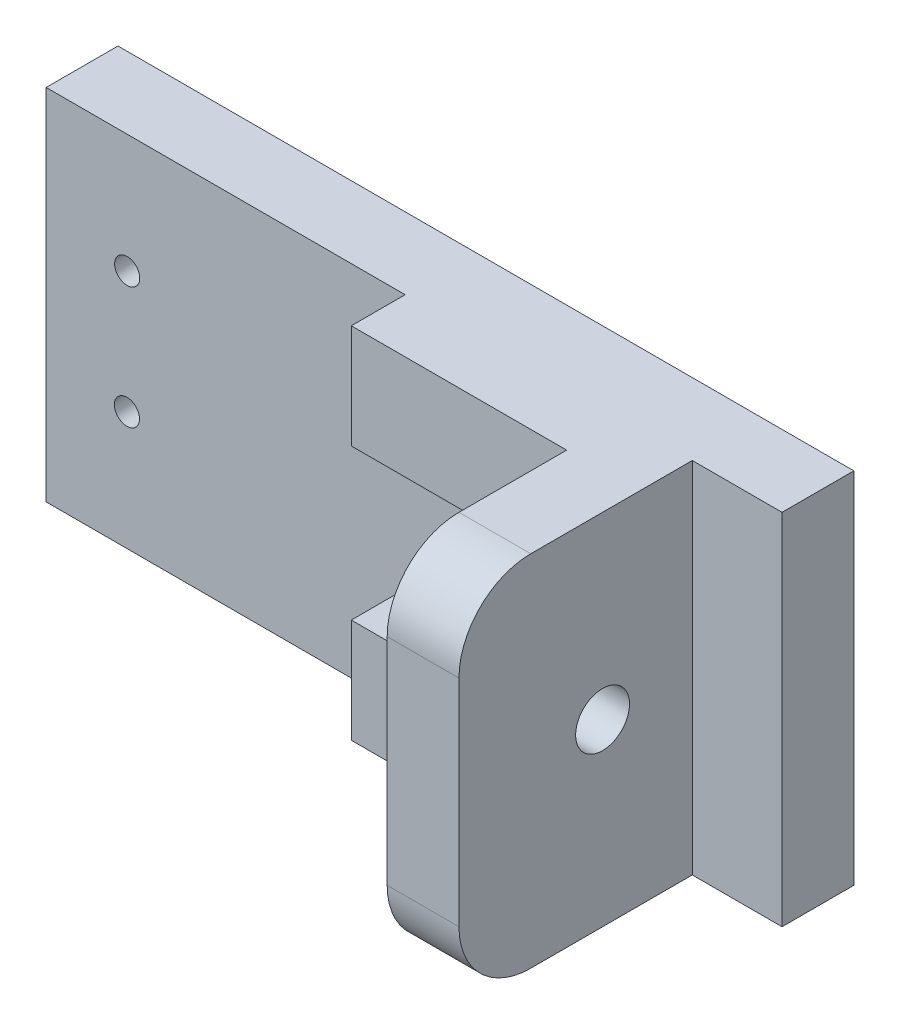
SolidWorks part; units mm, degrees
ref_plane "Piano frontale" through (0, 0, 0) normal (0, 0, 1) x (1, 0, 0)
ref_plane "Piano superiore" through (0, 0, 0) normal (0, 1, 0) x (1, 0, 0)
ref_plane "Piano destro" through (0, 0, 0) normal (1, 0, 0) x (0, 0, -1)
sketch "Schizzo1" plane through (0, 0, 0) normal (0, 0, 1) x (1, 0, 0)
  line L1 (-102.5, -50) -> (102.5, -50)
  line L2 (-102.5, -50) -> (-102.5, 50)
  line L3 (-102.5, 50) -> (102.5, 50)
  line L4 (102.5, -50) -> (102.5, 50)
  line L5 (-102.5, -50) -> (102.5, 50) construction
  line L6 (-102.5, 50) -> (102.5, -50) construction
  point P0 (0, 0)
  dimension "D1" = 205
  dimension "D2" = 100
extrude "Estrusione-Estrusione1" add sketch "Schizzo1" along normal blind 20
sketch "Schizzo2" plane through (0, 0, 0) normal (0, 0, 1) x (1, 0, 0)
  line L0 (-102.5, 50) -> (-102.5, -50) construction
  line L2 (-102.5, -50) -> (102.5, -50) construction
  circle A0 centre (-80, -17) radius 9.7421
  circle A1 centre (-79.9317, 16.9999) radius 9.7421
  dimension "D1" = 22.5
  dimension "D2" = 33
  dimension "D3" = 34
hole_wizard "Foro filettato M8x1.0-1" positions "Schizzo3" profile "Schizzo4" tap size "M8x1.0" standard "IS" end condition through all
sketch "Schizzo3" plane through (0, 0, 0) normal (0, 0, -1) x (-1, 0, 0)
  point P0 (79.9317, 16.9999)
  point P3 (80, -17)
cosmetic thread "Filettatura del foro1" parameters "D2"=8
cosmetic thread "Filettatura del foro2" parameters "D2"=8
sketch "Schizzo4" plane through (-79.9317, 16.9999, 0) normal (1, 0, 0) x (0, 1, 0)
  line L0 (0, 0) -> (0, 20)
  line L1 (0, 20) -> (3.5, 20)
  line L2 (3.5, 20) -> (3.5, 0)
  line L5 (3.5, 0) -> (0, 0)
  line L11 (0, -6.35) -> (0, 107.95) construction
  dimension "Thru Tap Drill Dia." = 7
  dimension "Thru Tap Drill Depth" = 20
sketch "Schizzo6" plane through (0, 0, 20) normal (0, 0, 1) x (1, 0, 0)
  line L0 (-102.5, -50) -> (102.5, -50) construction
  line L1 (57.5, -50) -> (-2.5, -50)
  line L2 (57.5, -50) -> (57.5, -21)
  line L3 (57.5, -21) -> (-2.5, -21)
  line L4 (-2.5, -50) -> (-2.5, -21)
  line L5 (102.5, -50) -> (102.5, 50) construction
  line L6 (11, 0) -> (-11, 0) construction
  line L7 (57.5, 21) -> (-2.5, 21)
  line L8 (-2.5, 50) -> (-2.5, 21)
  line L9 (57.5, 50) -> (-2.5, 50)
  line L10 (57.5, 50) -> (57.5, 21)
  dimension "D1" = 60
  dimension "D2" = 45
  dimension "D3" = 29
extrude "Estrusione-Estrusione2" add sketch "Schizzo6" along normal blind 15
sketch "Schizzo7" plane through (0, 0, 20) normal (0, 0, 1) x (1, 0, 0)
  line L0 (102.5, 50) -> (57.5, 50) construction
  line L1 (57.5, -50) -> (77.5, -50)
  line L2 (57.5, -50) -> (57.5, 50)
  line L3 (57.5, 50) -> (77.5, 50)
  line L4 (77.5, -50) -> (77.5, 50)
  line L5 (102.5, -50) -> (102.5, 50) construction
  dimension "D1" = 25
extrude "Estrusione-Estrusione3" add sketch "Schizzo7" along normal blind 65
sketch "Schizzo8" plane through (77.5, 0, 0) normal (1, 0, 0) x (0, 0, -1)
  circle A0 centre (-45, 0) radius 7.5
  dimension "D2" = 15
  dimension "D1" = 45
extrude "Taglio-Estrusione1" cut sketch "Schizzo8" against normal through all
fillet "Raccordo1" radius 20 2 edges at (67.5, 50, 85) (67.5, -50, 85)
